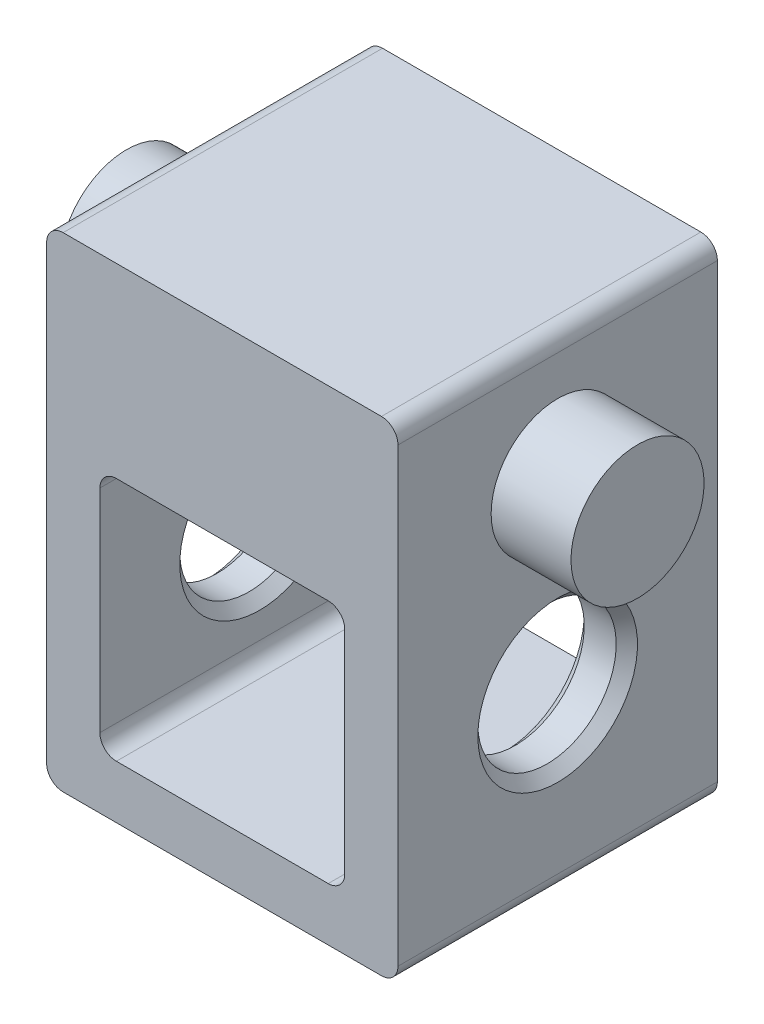
SolidWorks part; units mm, degrees
material "7075-O (SS)"
ref_plane "Front Plane" through (0, 0, 0) normal (0, 0, 1) x (1, 0, 0)
ref_plane "Top Plane" through (0, 0, 0) normal (0, 1, 0) x (1, 0, 0)
ref_plane "Right Plane" through (0, 0, 0) normal (1, 0, 0) x (0, 0, -1)
sketch "Sketch1" plane through (0, 0, 0) normal (0, 0, 1) x (1, 0, 0)
  line L1 (-33, -33) -> (33, -33)
  line L2 (-33, -33) -> (-33, 33)
  line L3 (-33, 33) -> (33, 33)
  line L4 (33, -33) -> (33, 33)
  line L5 (-33, -33) -> (33, 33) construction
  line L6 (-33, 33) -> (33, -33) construction
  point P0 (0, 0)
  dimension "D1" = 66
  dimension "D2" = 66
extrude "Boss-Extrude1" add sketch "Sketch1" along normal blind 60
shell "Shell1" thickness 10
fillet "Fillet2" radius 3.1 4 edges at (23, -23, 30) (-23, -23, 30) (23, 23, 30) (-23, 23, 30)
sketch "Sketch2" plane through (33, 0, 0) normal (1, 0, 0) x (0, 0, -1)
  line L0 (-60, 33) -> (0, 33)
  line L1 (0, 33) -> (0, 58)
  line L2 (0, 58) -> (-60, 58)
  line L3 (-60, 58) -> (-60, 33)
  dimension "D1" = 25
extrude "Boss-Extrude2" add sketch "Sketch2" against normal up to surface (66 mm away) up to face at (-33, 0, 30)
fillet "Fillet3" radius 3.1 4 edges at (33, -33, 30) (-33, -33, 30) (-33, 58, 30) (33, 58, 30)
sketch "Sketch3" plane through (0, 0, 0) normal (1, 0, 0) x (0, 0, -1)
  line L0 (-30, 54.9) -> (-30, -29.9) construction
  line L1 (0, 54.9) -> (-60, 54.9) construction
  line L2 (-60, -29.9) -> (0, -29.9) construction
  circle A0 centre (-30, 34.9529) radius 12.5
  dimension "D1" = 25
extrude "Boss-Extrude4" add sketch "Sketch3" along normal offset from surface 15 and the other way offset from surface (48 mm away) 15 up to face at (33, 12.5, 30) offset beyond the face yes other way up to face at (-33, 12.5, 30)
sketch "Sketch4" plane through (23, 0, 0) normal (-1, 0, 0) x (0, 0, 1)
  line L0 (30, 23) -> (30, -23) construction
  line L1 (60, 23) -> (0, 23) construction
  line L2 (60, -23) -> (0, -23) construction
  circle A0 centre (30, 0) radius 13
  dimension "D1" = 26
extrude "Cut-Extrude1" cut sketch "Sketch4" against normal through all both and the other way through all
chamfer "Chamfer1" distance 2 angle 45 4 edges at (23, 0, 43) (-23, 0, 17) (-33, 0, 17) (33, 0, 43)
